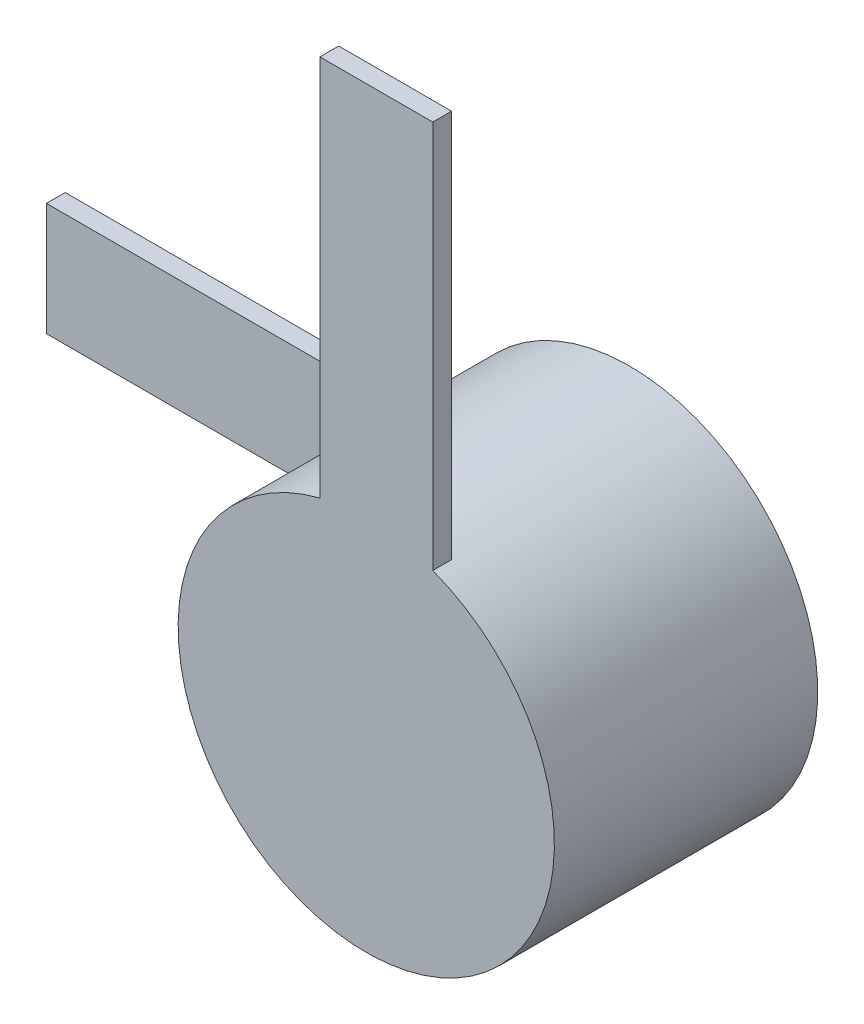
SolidWorks part; units mm, degrees
ref_plane "Front Plane" through (0, 0, 0) normal (0, 0, 1) x (1, 0, 0)
ref_plane "Top Plane" through (0, 0, 0) normal (0, 1, 0) x (1, 0, 0)
ref_plane "Right Plane" through (0, 0, 0) normal (1, 0, 0) x (0, 0, -1)
sketch "Sketch1" plane through (0, 0, 0) normal (0, 0, 1) x (1, 0, 0)
  circle A0 centre (0, 0) radius 50
  dimension "D1" = 100
extrude "Boss-Extrude1" add sketch "Sketch1" along normal blind 70
sketch "Sketch2" plane through (0, 0, 0) normal (0, 1, 0) x (1, 0, 0)
  line L0 (-50, -70) -> (50, -70) construction
  line L1 (-12.3267, -70) -> (17.6733, -70)
  line L2 (-12.3267, -70) -> (-12.3267, -65)
  line L3 (-12.3267, -65) -> (17.6733, -65)
  line L4 (17.6733, -70) -> (17.6733, -65)
  dimension "D1" = 30
  dimension "D2" = 5
extrude "Boss-Extrude2" add sketch "Sketch2" along normal blind 150
sketch "Sketch4" plane through (0, 0, 0) normal (1, 0, 0) x (0, 0, -1)
  line L0 (0, -50) -> (0, 50) construction
  line L1 (0, 14.9401) -> (-5, 14.9401)
  line L2 (0, 14.9401) -> (0, -15.0599)
  line L3 (0, -15.0599) -> (-5, -15.0599)
  line L4 (-5, 14.9401) -> (-5, -15.0599)
  dimension "D1" = 30
  dimension "D2" = 5
extrude "Boss-Extrude3" add sketch "Sketch4" against normal blind 150
